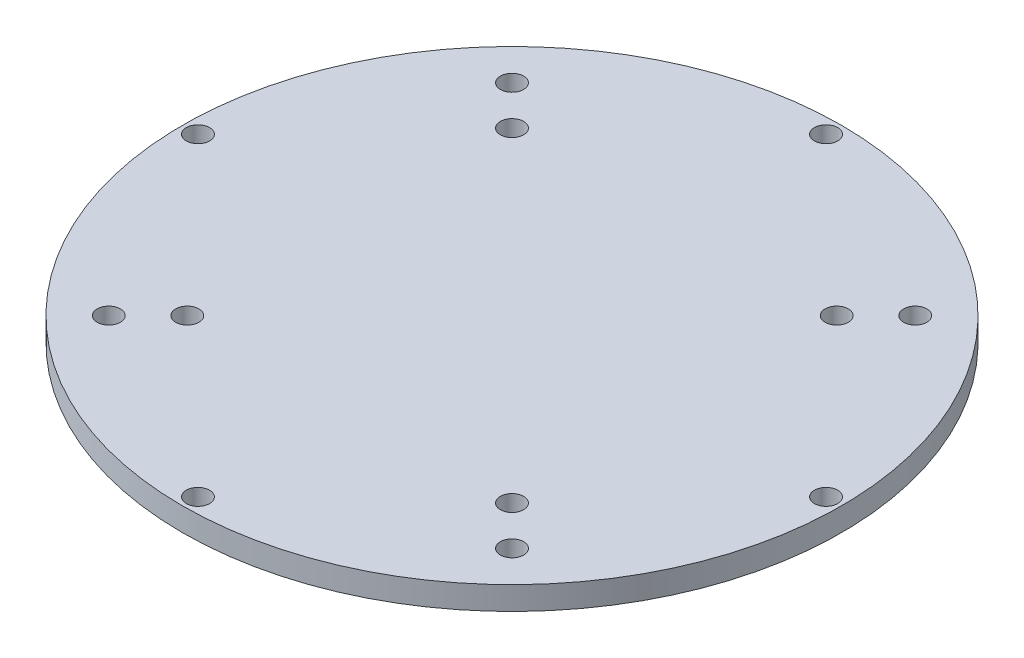
SolidWorks part; units mm, degrees
ref_plane "前视基准面" through (0, 0, 0) normal (0, 0, 1) x (1, 0, 0)
ref_plane "上视基准面" through (0, 0, 0) normal (0, 1, 0) x (1, 0, 0)
ref_plane "右视基准面" through (0, 0, 0) normal (1, 0, 0) x (0, 0, -1)
sketch "草图1" plane through (0, 0, 0) normal (0, 1, 0) x (1, 0, 0)
  line L0 (0, 0) -> (0, 40.5) construction
  line L5 (0, 0) -> (-20.9374, 20.9374) construction
  line L7 (-26, -26) -> (26, -26) construction
  line L8 (-26, -26) -> (-26, 26) construction
  line L9 (-26, 26) -> (26, 26) construction
  line L10 (26, -26) -> (26, 26) construction
  circle A0 centre (-26, 26) radius 1.5
  circle A1 centre (26, 26) radius 1.5
  circle A2 centre (26, -26) radius 1.5
  circle A3 centre (-26, -26) radius 1.5
  circle A8 centre (0, 0) radius 42.5
  circle A9 centre (0, 40.5) radius 1.5
  circle A10 centre (40.5, 0) radius 1.5
  circle A11 centre (0, -40.5) radius 1.5
  circle A12 centre (-40.5, 0) radius 1.5
  circle A13 centre (-20.9374, 20.9374) radius 1.5
  circle A14 centre (20.9374, 20.9374) radius 1.5
  circle A15 centre (20.9374, -20.9374) radius 1.5
  circle A16 centre (-20.9374, -20.9374) radius 1.5
  point P0 (0, 0)
  point P5 (0, 0)
  point P14 (-30, -30)
  point P21 (0, 0)
  point P28 (-30, 30)
  point P38 (0, 0)
  dimension "D3" = 3
  dimension "D5" = 40.5
  dimension "D6" = 85
  dimension "D7" = 3
  dimension "D10" = 3
  dimension "D1" = 60
  dimension "D2" = 52
  dimension "D9" = 29.61
  dimension "D4" = 4
  dimension "D8" = 4
  dimension "D11" = 4
extrude "凸台-拉伸1" add sketch "草图1" along normal blind 3
